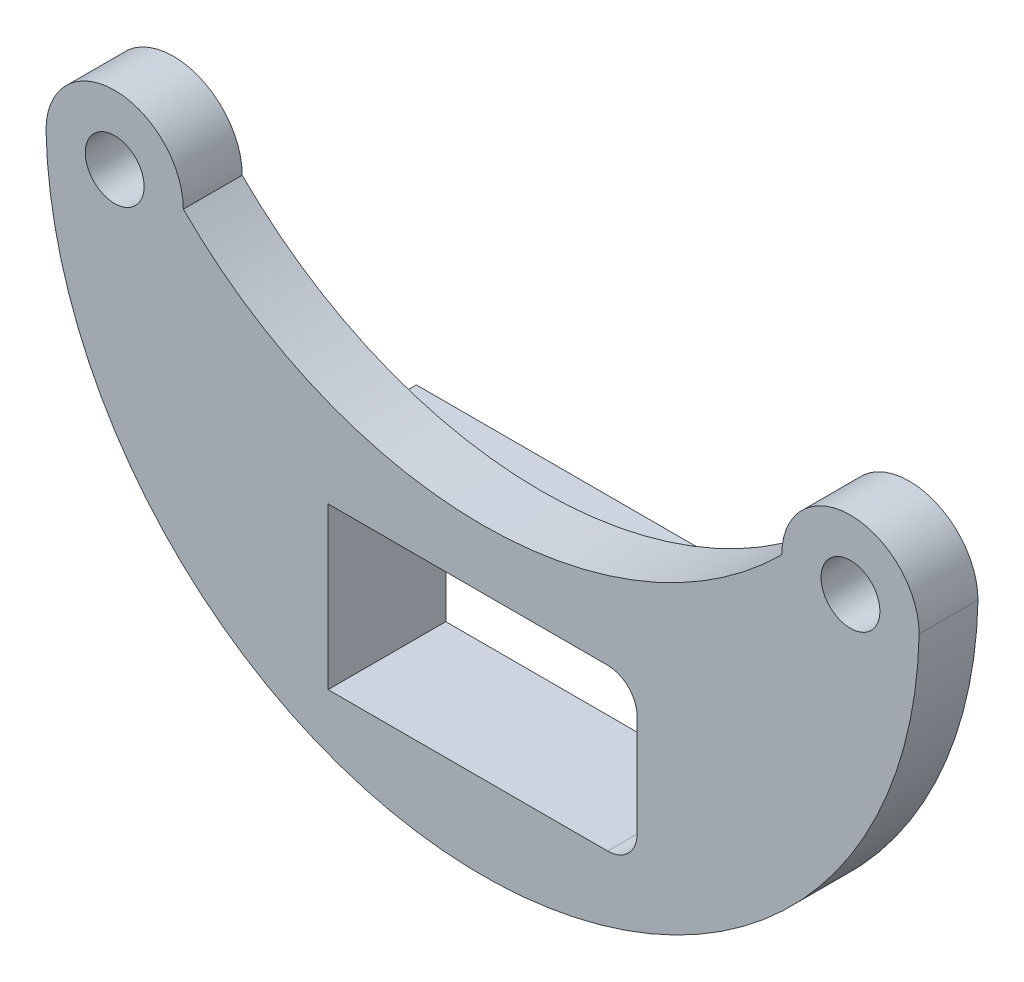
SolidWorks part; units mm, degrees
ref_plane "Alzado" through (0, 0, 0) normal (0, 0, 1) x (1, 0, 0)
ref_plane "Planta" through (0, 0, 0) normal (0, 1, 0) x (1, 0, 0)
ref_plane "Vista lateral" through (0, 0, 0) normal (1, 0, 0) x (0, 0, -1)
sketch "Croquis1" plane through (0, 0, 0) normal (0, 0, 1) x (1, 0, 0)
  line L0 (-64.1209, 5.4598) -> (-26.6209, 5.4598) construction
  line L1 (-26.6209, 5.4598) -> (-45.3709, 5.4598) construction
  line L2 (-45.3709, 5.4598) -> (-45.3709, 1.4598) construction
  line L3 (-45.3709, -0.857) -> (-45.3709, -3.857) construction
  line L4 (-45.3709, -3.857) -> (-38.9959, -3.857)
  line L5 (-37.4959, -5.357) -> (-37.4959, -10.557)
  line L6 (-38.9959, -12.057) -> (-53.2459, -12.057)
  line L7 (-53.2459, -12.057) -> (-53.2459, -3.857)
  line L8 (-53.2459, -3.857) -> (-38.9959, -3.857)
  circle A0 centre (-64.1209, 5.4598) radius 1.5
  circle A1 centre (-26.6209, 5.4598) radius 1.5
  arc A2 (-60.6209, 5.4598) -> (-67.6165, 5.285) centre (-64.1209, 5.4598) ccw
  arc A3 (-23.1253, 5.285) -> (-30.1209, 5.4598) centre (-26.6209, 5.4598) ccw
  arc A4 (-60.6209, 5.4598) -> (-30.1209, 5.4598) centre (-45.3709, 20.7098) ccw
  arc A5 (-37.4959, -10.557) -> (-38.9959, -12.057) centre (-38.9959, -10.557) cw
  arc A6 (-37.4959, -5.357) -> (-38.9959, -3.857) centre (-38.9959, -5.357) ccw
  arc A7 (-67.6209, 5.4598) -> (-23.1209, 5.4598) centre (-45.3709, 5.9283) ccw
  dimension "D1" = 37.5
  dimension "D2" = 1.5
  dimension "D3" = 3
  dimension "D4" = 3
extrude "Saliente-Extruir1" add sketch "Croquis1" along normal blind 3 contours A2 A7 A3 A4 A0 A1 A6 L5 A5 L6 L7 L8 L4
sketch "Croquis2" plane through (0, 0, 0) normal (0, 0, -1) x (-1, 0, 0)
  line L0 (38.9959, -12.057) -> (53.2459, -12.057)
  line L1 (53.2459, -12.057) -> (53.2459, -3.857)
  line L2 (53.2459, -3.857) -> (38.9959, -3.857)
  line L3 (37.4959, -10.557) -> (37.4959, -5.357)
  line L5 (54.7459, -13.557) -> (35.9959, -13.557)
  line L6 (54.7459, -13.557) -> (54.7459, -2.357)
  line L7 (54.7459, -2.357) -> (35.9959, -2.357)
  line L8 (35.9959, -13.557) -> (35.9959, -2.357)
  arc A0 (38.9959, -3.857) -> (37.4959, -5.357) centre (38.9959, -5.357) ccw
  arc A1 (37.4959, -10.557) -> (38.9959, -12.057) centre (38.9959, -10.557) ccw
  dimension "D1" = 1.5
  dimension "D2" = 1.5
  dimension "D3" = 1.5
  dimension "D4" = 1.5
extrude "Saliente-Extruir2" add sketch "Croquis2" along normal blind 3
